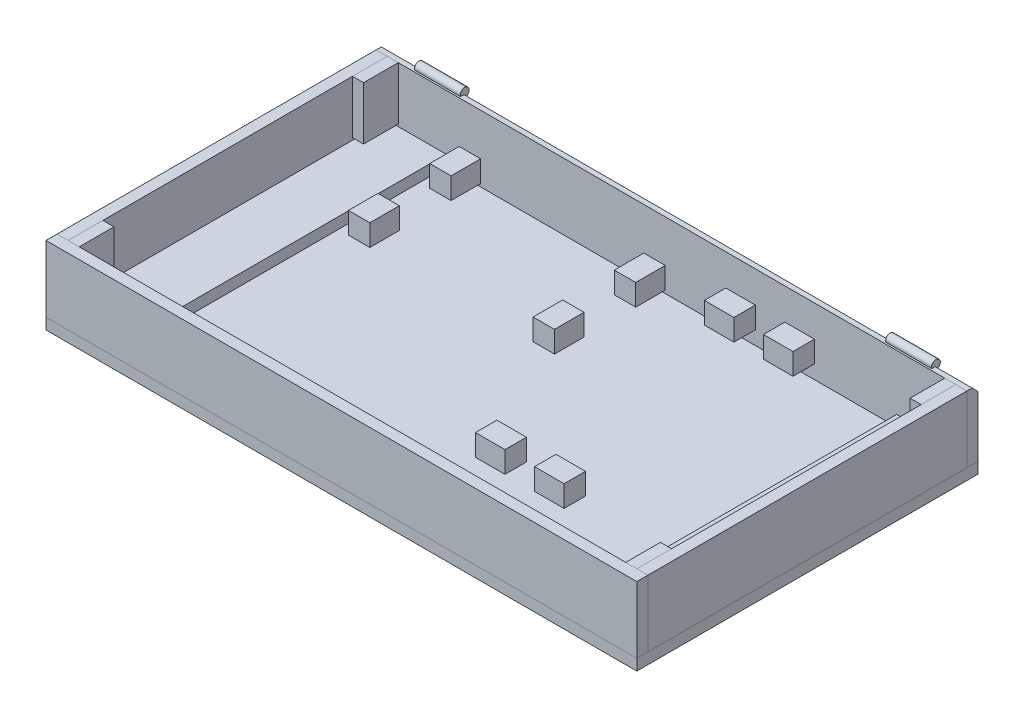
SolidWorks part; units mm, degrees
material "Pin"
ref_plane "Front" through (0, 0, 0) normal (0, 0, 1) x (1, 0, 0)
ref_plane "Top" through (0, 0, 0) normal (0, 1, 0) x (1, 0, 0)
ref_plane "Right" through (0, 0, 0) normal (1, 0, 0) x (0, 0, -1)
sketch "Esquisse1" plane through (0, 0, 0) normal (0, 1, 0) x (1, 0, 0)
  line L1 (-400, -231) -> (400, -231)
  line L2 (-400, -231) -> (-400, 231)
  line L3 (-400, 231) -> (400, 231)
  line L4 (400, -231) -> (400, 231)
  line L5 (0, 231) -> (0, -231) construction
  line L6 (-400, 0) -> (400, 0) construction
  point P0 (0, 0)
  dimension "D1" = 462
  dimension "D2" = 800
extrude "Boss.-Extru.1" add sketch "Esquisse1" along normal blind 15
sketch "Esquisse3" plane through (0, 15, 0) normal (0, 1, 0) x (1, 0, 0)
  line L0 (400, -231) -> (400, 231) construction
  line L1 (-400, 231) -> (400, 231)
  line L2 (-400, 231) -> (-400, 216)
  line L3 (-400, 216) -> (400, 216)
  line L4 (400, 231) -> (400, 216)
  line L5 (-50, 0) -> (50, 0) construction
  line L6 (400, -231) -> (400, -216)
  line L7 (-400, -216) -> (400, -216)
  line L8 (-400, -231) -> (-400, -216)
  line L9 (-400, -231) -> (400, -231)
  dimension "D1" = 15
extrude "Boss.-Extru.3" add sketch "Esquisse3" along normal blind 90 separate body
sketch "Esquisse4" plane through (0, 15, 0) normal (0, 1, 0) x (1, 0, 0)
  line L0 (400, -216) -> (-400, -216) construction
  line L1 (-400, 216) -> (-385, 216)
  line L2 (-400, 216) -> (-400, -216)
  line L3 (-400, -216) -> (-385, -216)
  line L4 (-385, 216) -> (-385, -216)
  line L5 (-400, -216) -> (-400, -231) construction
  line L6 (400, 216) -> (385, 216)
  line L7 (400, 216) -> (400, -216)
  line L8 (400, -216) -> (385, -216)
  line L9 (385, 216) -> (385, -216)
extrude "Boss.-Extru.4" add sketch "Esquisse4" along normal up to vertex (90 mm away) separate body
sketch "Esquisse5" plane through (0, 105, 0) normal (0, 1, 0) x (1, 0, 0)
  line L0 (-50, 0) -> (50, 0) construction
  line L1 (-385, 216) -> (-370, 216)
  line L2 (-385, 216) -> (-385, 169)
  line L3 (-385, 169) -> (-370, 169)
  line L4 (-370, 216) -> (-370, 169)
  line L5 (-370, -216) -> (-370, -169)
  line L6 (-385, -169) -> (-370, -169)
  line L7 (-385, -216) -> (-385, -169)
  line L8 (-385, -216) -> (-370, -216)
  line L9 (0, -50) -> (0, 50) construction
  line L10 (385, -216) -> (370, -216)
  line L11 (385, -216) -> (385, -169)
  line L12 (385, -169) -> (370, -169)
  line L13 (370, -216) -> (370, -169)
  line L14 (370, 216) -> (370, 169)
  line L15 (385, 169) -> (370, 169)
  line L16 (385, 216) -> (385, 169)
  line L17 (385, 216) -> (370, 216)
  dimension "D1" = 15
  dimension "D2" = 47
extrude "Boss.-Extru.5" add sketch "Esquisse5" against normal offset from surface (72 mm away) 18 from offset 0 separate body up to face at (0, 15, 0)
sketch "Esquisse7" plane through (0, 15, 0) normal (0, 1, 0) x (1, 0, 0)
  line L28 (400, -216) -> (-400, -216) construction
  line L29 (-385, 216) -> (-305, 216)
  line L30 (-385, 216) -> (-385, -216)
  line L31 (-385, -216) -> (-305, -216)
  line L32 (-305, 216) -> (-305, -216)
  line L33 (0, -50) -> (0, 50) construction
  line L34 (305, 216) -> (305, -216)
  line L35 (385, -216) -> (305, -216)
  line L36 (385, 216) -> (385, -216)
  line L37 (385, 216) -> (305, 216)
  dimension "D1" = 80
extrude "Boss.-Extru.6" add sketch "Esquisse7" along normal blind 15 separate body
sketch "Esquisse8" plane through (-400, 0, 0) normal (-1, 0, 0) x (0, 0, 1)
  line L1 (-216, 105) -> (-216, 15) construction
  line L2 (-231, 105) -> (-216, 105) construction
  circle A0 centre (-224, 107) radius 6
  point P2 (-224, 111.1315)
  dimension "D1" = 12
  dimension "D2" = 8
  dimension "D3" = 2
extrude "Boss.-Extru.7" add sketch "Esquisse8" against normal blind 62 from offset 50 separate body offset against normal yes
mirror "Symétrie3" about plane through (0, 0, 0) normal (1, 0, 0) of bodies 116
chamfer "Chanfrein1" distance 8 angle 45 1 edges at (0, 105, -231)
sketch "Esquisse9" plane through (0, 15, 0) normal (0, 1, 0) x (1, 0, 0)
  line L0 (135, -15) -> (255, -15) construction
  line L1 (135, 154.5) -> (255, 154.5)
  line L2 (135, 154.5) -> (135, 125.5)
  line L3 (135, 125.5) -> (255, 125.5)
  line L4 (255, 154.5) -> (255, 125.5)
  line L5 (255, -184.5) -> (255, -155.5)
  line L6 (135, -155.5) -> (255, -155.5)
  line L7 (135, -184.5) -> (135, -155.5)
  line L8 (135, -184.5) -> (255, -184.5)
  line L9 (-72, 140) -> (-72, -10) construction
  line L10 (-211.5, 140) -> (-182.5, 140)
  line L11 (-211.5, 140) -> (-211.5, -10)
  line L12 (-211.5, -10) -> (-182.5, -10)
  line L13 (-182.5, 140) -> (-182.5, -10)
  line L14 (38.5, 140) -> (38.5, -10)
  line L15 (67.5, -10) -> (38.5, -10)
  line L16 (67.5, 140) -> (67.5, -10)
  line L17 (67.5, 140) -> (38.5, 140)
  line L18 (385, -216) -> (385, 216) construction
  line L19 (-400, 216) -> (400, 216) construction
  point P20 (195, -15)
  point P25 (-72, 65)
  dimension "D1" = 120
  dimension "D2" = 190
  dimension "D3" = 339
  dimension "D4" = 231
  dimension "D5" = 29
  dimension "D6" = 279
  dimension "D7" = 457
  dimension "D8" = 151
  dimension "D9" = 150
extrude "Boss.-Extru.8" add sketch "Esquisse9" along normal blind 29 from offset 0 separate body
move or copy body "Corps-Déplacer/Copier1" bodies to move or copy 127 126 121 128 copy no translate (0, 80, 0)
sketch "Esquisse10" plane through (0, 124, 0) normal (0, 1, 0) x (1, 0, 0)
  line L0 (-211.5, 140) -> (-211.5, -10) construction
  line L1 (-211.5, 100) -> (67.5, 100)
  line L2 (-211.5, 100) -> (-211.5, 30)
  line L3 (-211.5, 30) -> (67.5, 30)
  line L4 (67.5, 100) -> (67.5, 30)
  line L5 (255, 154.5) -> (135, 154.5) construction
  line L6 (175, 154.5) -> (215, 154.5)
  line L7 (175, 154.5) -> (175, -184.5)
  line L8 (175, -184.5) -> (215, -184.5)
  line L9 (215, 154.5) -> (215, -184.5)
  line L10 (135, -184.5) -> (255, -184.5) construction
  line L11 (67.5, -10) -> (67.5, 140) construction
  line L12 (-182.5, 140) -> (-211.5, 140) construction
  line L13 (135, 154.5) -> (135, 125.5) construction
  point P12 (195, -184.5)
  point P15 (67.5, 65)
  dimension "D1" = 40
  dimension "D2" = 40
extrude "Enlèv. mat.-Extru.1" cut sketch "Esquisse10" against normal through all
